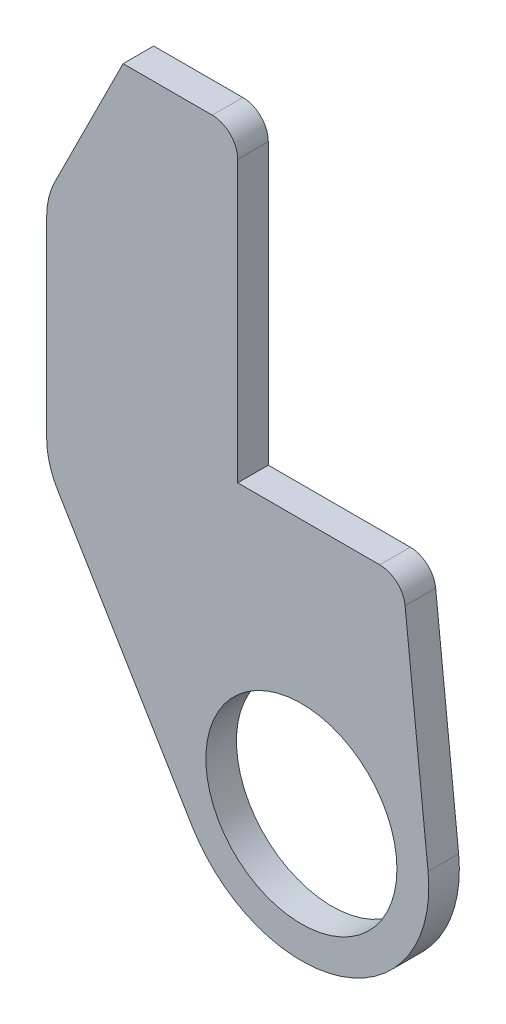
SolidWorks part; units mm, degrees
material "Q355"
ref_plane "前视基准面" through (0, 0, 0) normal (0, 0, 1) x (1, 0, 0)
ref_plane "上视基准面" through (0, 0, 0) normal (0, 1, 0) x (1, 0, 0)
ref_plane "右视基准面" through (0, 0, 0) normal (1, 0, 0) x (0, 0, -1)
sketch "草图1" plane through (0, 0, 0) normal (0, 0, 1) x (1, 0, 0)
  line L0 (-42.8584, -25.7519) -> (-100, 69.3477)
  line L1 (-100, 69.3477) -> (-100, 160)
  line L2 (-100, 160) -> (-70, 220)
  line L3 (-70, 220) -> (-25, 220)
  line L4 (-25, 220) -> (-25, 100)
  line L5 (-25, 100) -> (39.765, 100)
  line L6 (39.765, 100) -> (49.7261, 5.2264)
  circle A0 centre (0, 0) radius 37.5
  arc A1 (-42.8584, -25.7519) -> (49.7261, 5.2264) centre (0, 0) ccw
  dimension "D1" = 75
  dimension "D2" = 100
  dimension "D3" = 25
  dimension "D4" = 100
  dimension "D5" = 6
  dimension "D6" = 75
  dimension "D7" = 120
  dimension "D8" = 60
  dimension "D9" = 30
  dimension "D10" = 31
extrude "凸台-拉伸1" add sketch "草图1" along normal blind 12
fillet "圆角1" radius 10 2 edges at (-25, 220, 6) (39.765, 100, 6)
fillet "圆角2" radius 30 2 edges at (-100, 160, 6) (-100, 69.3477, 6)
